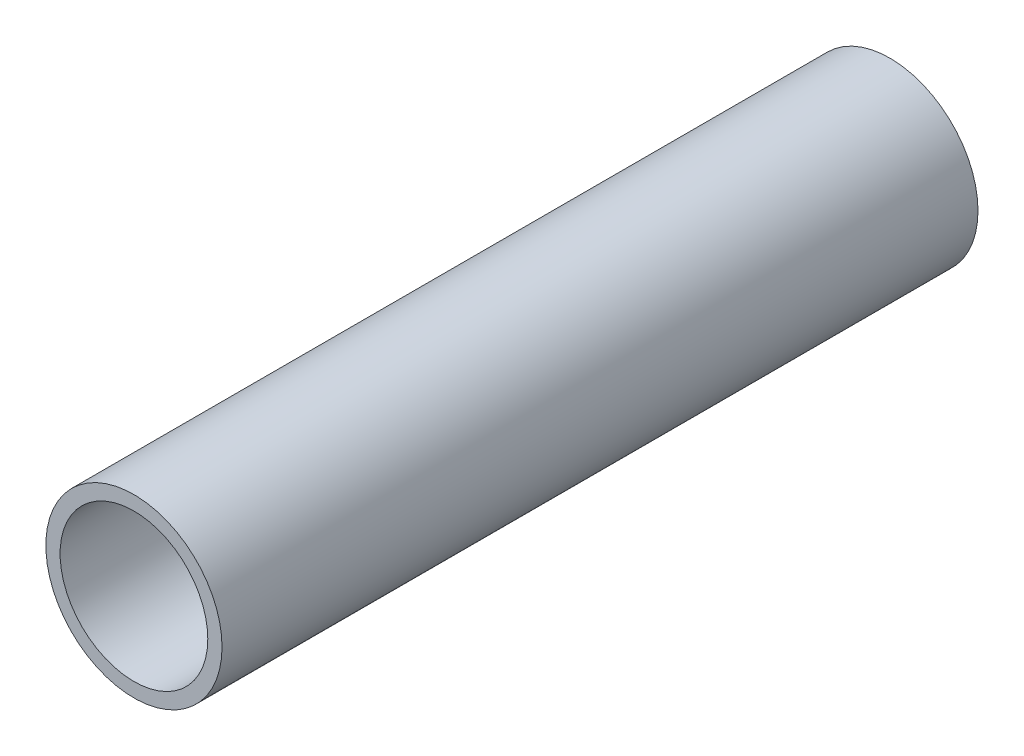
SolidWorks part; units mm, degrees
ref_plane "Front Plane" through (0, 0, 0) normal (0, 0, 1) x (1, 0, 0)
ref_plane "Top Plane" through (0, 0, 0) normal (0, 1, 0) x (1, 0, 0)
ref_plane "Right Plane" through (0, 0, 0) normal (1, 0, 0) x (0, 0, -1)
sketch "Sketch1" plane through (0, 0, 0) normal (0, 0, 1) x (1, 0, 0)
  circle A0 centre (0, 0) radius 25.4
  circle A1 centre (0, 0) radius 30.3
  dimension "D1" = 50.8
  dimension "D2" = 60.6
extrude "Boss-Extrude1" add sketch "Sketch1" along normal blind 260
